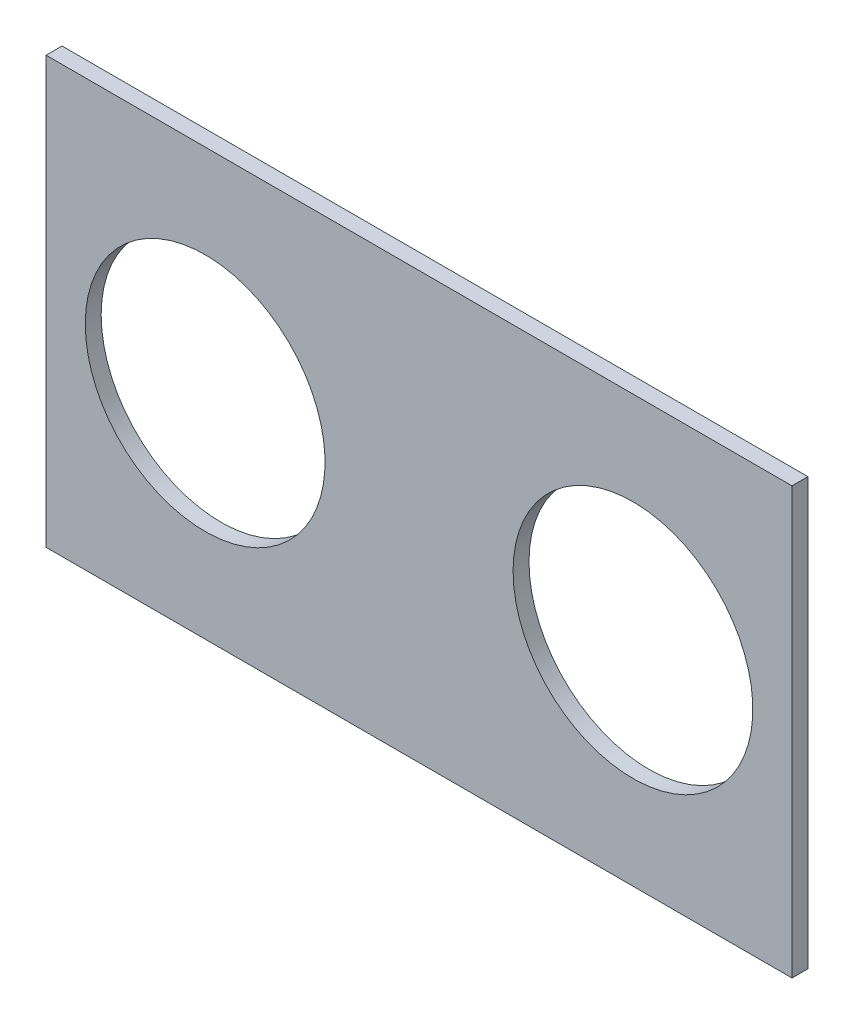
SolidWorks part; units mm, degrees
material "Plain Carbon Steel"
ref_plane "Front Plane" through (0, 0, 0) normal (0, 0, 1) x (1, 0, 0)
ref_plane "Top Plane" through (0, 0, 0) normal (0, 1, 0) x (1, 0, 0)
ref_plane "Right Plane" through (0, 0, 0) normal (1, 0, 0) x (0, 0, -1)
sketch "Sketch1" plane through (0, 0, 0) normal (0, 0, 1) x (1, 0, 0)
  line L0 (-18.9548, 0) -> (69.9452, 0) construction
  line L1 (-18.9548, 25.4) -> (69.9452, 25.4)
  line L2 (-18.9548, 25.4) -> (-18.9547, -25.4)
  line L3 (-18.9547, -25.4) -> (69.9452, -25.4)
  line L4 (69.9452, 25.4) -> (69.9452, -25.4)
  line L5 (25.4953, 25.4) -> (25.4953, -25.4) construction
  circle A0 centre (0, 0) radius 14.2875 construction
  circle A1 centre (50.9905, 0) radius 14.2875 construction
  circle A2 centre (0, 0) radius 14.2875
  circle A3 centre (50.9905, 0) radius 14.2875
  dimension "D1" = 50.8
  dimension "D2" = 88.9
extrude "Boss-Extrude1" add sketch "Sketch1" along normal blind 1.8974
